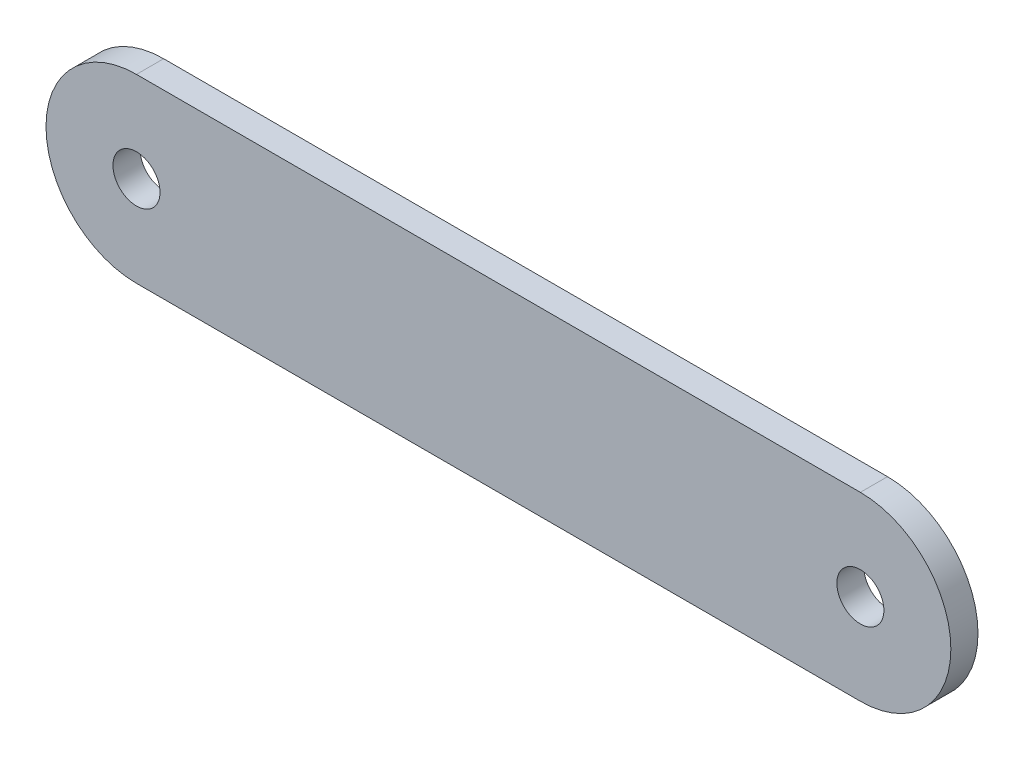
SolidWorks part; units mm, degrees
ref_plane "前视基准面" through (0, 0, 0) normal (0, 0, 1) x (1, 0, 0)
ref_plane "上视基准面" through (0, 0, 0) normal (0, 1, 0) x (1, 0, 0)
ref_plane "右视基准面" through (0, 0, 0) normal (1, 0, 0) x (0, 0, -1)
sketch "草图1" plane through (0, 0, 0) normal (0, 0, 1) x (1, 0, 0)
  line L0 (-47.6808, 0) -> (55.5577, 0) construction
  line L1 (0, 30.2024) -> (0, -22.5382) construction
  line L2 (-40, 0) -> (40, 0) construction
  line L3 (-40, 10) -> (40, 10)
  line L4 (-40, -10) -> (40, -10)
  circle A1 centre (-40, 0) radius 2.6
  circle A2 centre (40, 0) radius 2.6
  arc A3 (-40, 10) -> (-40, -10) centre (-40, 0) ccw
  arc A4 (40, -10) -> (40, 10) centre (40, 0) ccw
  point P11 (0, 0)
  dimension "D2" = 5.2
  dimension "D3" = 80
  dimension "D4" = 20
extrude "凸台-拉伸1" add sketch "草图1" along normal blind 3
